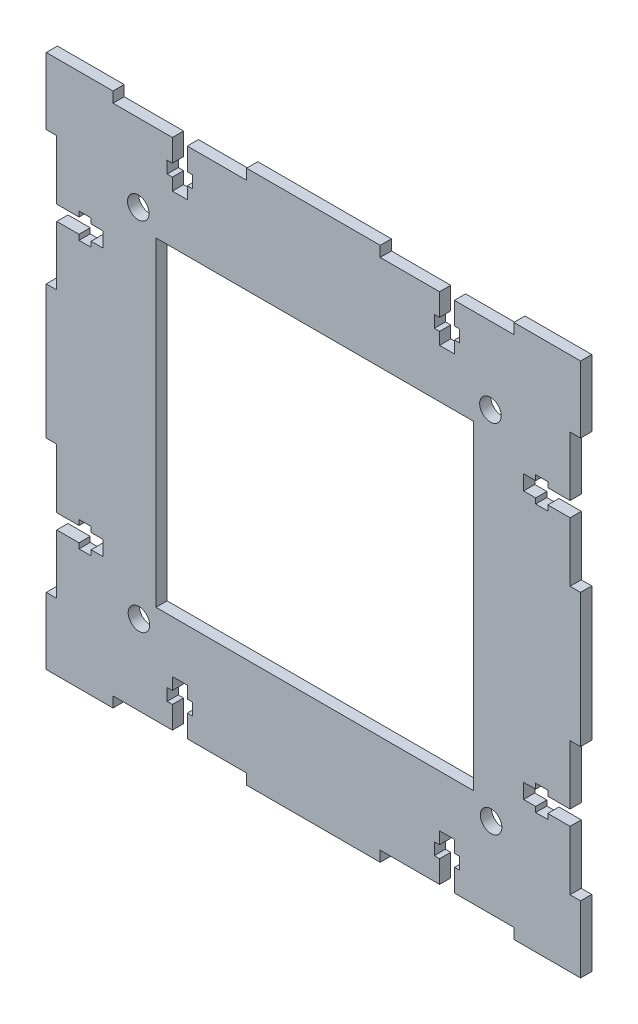
SolidWorks part; units mm, degrees
ref_plane "Front Plane" through (0, 0, 0) normal (0, 0, 1) x (1, 0, 0)
ref_plane "Top Plane" through (0, 0, 0) normal (0, 1, 0) x (1, 0, 0)
ref_plane "Right Plane" through (0, 0, 0) normal (1, 0, 0) x (0, 0, -1)
sketch "Sketch1" plane through (0, 0, 0) normal (0, 0, 1) x (1, 0, 0)
  line L5 (31.0877, 278.8269) -> (31.0877, 188.1807)
  line L12 (31.0877, 188.1807) -> (121.0608, 188.1807)
  line L13 (121.0608, 278.8269) -> (121.0608, 188.1807)
  line L14 (31.0877, 278.8269) -> (121.0608, 278.8269)
  line L312 (0, 308.795) -> (0, 289.8679)
  line L313 (0, 289.8679) -> (2.9806, 289.8679)
  line L314 (2.9806, 289.8679) -> (2.9806, 273.0521)
  line L315 (2.9806, 273.0521) -> (9.2897, 273.0521)
  line L316 (9.2897, 273.0521) -> (9.2897, 274.5424)
  line L317 (9.2897, 274.5424) -> (12.7174, 274.5424)
  line L318 (12.7174, 274.5424) -> (12.7174, 273.0521)
  line L319 (12.7174, 273.0521) -> (16.1452, 273.0521)
  line L320 (16.1452, 273.0521) -> (16.1452, 268.8295)
  line L321 (16.1452, 268.8295) -> (12.7174, 268.8295)
  line L322 (12.7174, 268.8295) -> (12.7174, 267.3392)
  line L323 (12.7174, 267.3392) -> (9.2897, 267.3392)
  line L324 (9.2897, 267.3392) -> (9.2897, 268.8295)
  line L325 (9.2897, 268.8295) -> (2.9806, 268.8295)
  line L326 (2.9806, 268.8295) -> (2.9806, 252.0137)
  line L327 (2.9806, 252.0137) -> (0, 252.0137)
  line L328 (0, 252.0137) -> (0, 214.1595)
  line L329 (0, 214.1595) -> (2.9806, 214.1595)
  line L330 (2.9806, 214.1595) -> (2.9806, 197.3437)
  line L331 (2.9806, 197.3437) -> (9.2897, 197.3437)
  line L332 (9.2897, 197.3437) -> (9.2897, 198.834)
  line L333 (9.2897, 198.834) -> (12.7174, 198.834)
  line L334 (12.7174, 198.834) -> (12.7174, 197.3437)
  line L335 (12.7174, 197.3437) -> (16.1452, 197.3437)
  line L336 (16.1452, 197.3437) -> (16.1452, 193.1211)
  line L337 (16.1452, 193.1211) -> (12.7174, 193.1211)
  line L338 (12.7174, 193.1211) -> (12.7174, 191.6307)
  line L339 (12.7174, 191.6307) -> (9.2897, 191.6307)
  line L340 (9.2897, 191.6307) -> (9.2897, 193.1211)
  line L341 (9.2897, 193.1211) -> (2.9806, 193.1211)
  line L342 (2.9806, 193.1211) -> (2.9806, 176.3053)
  line L343 (2.9806, 176.3053) -> (0, 176.3053)
  line L344 (0, 176.3053) -> (0, 157.3781)
  line L345 (0, 157.3781) -> (18.9271, 157.3781)
  line L346 (18.9271, 157.3781) -> (18.9271, 160.3588)
  line L347 (18.9271, 160.3588) -> (35.7429, 160.3588)
  line L348 (35.7429, 160.3588) -> (35.7429, 166.6678)
  line L349 (35.7429, 166.6678) -> (34.2526, 166.6678)
  line L350 (34.2526, 166.6678) -> (34.2526, 170.0956)
  line L351 (34.2526, 170.0956) -> (35.7429, 170.0956)
  line L352 (35.7429, 170.0956) -> (35.7429, 173.5233)
  line L353 (35.7429, 173.5233) -> (39.9655, 173.5233)
  line L354 (39.9655, 173.5233) -> (39.9655, 170.0956)
  line L355 (39.9655, 170.0956) -> (41.4558, 170.0956)
  line L356 (41.4558, 170.0956) -> (41.4558, 166.6678)
  line L357 (41.4558, 166.6678) -> (39.9655, 166.6678)
  line L358 (39.9655, 166.6678) -> (39.9655, 160.3588)
  line L359 (39.9655, 160.3588) -> (56.7813, 160.3588)
  line L360 (56.7813, 160.3588) -> (56.7813, 157.3781)
  line L361 (56.7813, 157.3781) -> (94.6355, 157.3781)
  line L362 (94.6355, 157.3781) -> (94.6355, 160.3588)
  line L363 (94.6355, 160.3588) -> (111.4513, 160.3588)
  line L364 (111.4513, 160.3588) -> (111.4513, 166.6678)
  line L365 (111.4513, 166.6678) -> (109.961, 166.6678)
  line L366 (109.961, 166.6678) -> (109.961, 170.0956)
  line L367 (109.961, 170.0956) -> (111.4513, 170.0956)
  line L368 (111.4513, 170.0956) -> (111.4513, 173.5233)
  line L369 (111.4513, 173.5233) -> (115.6739, 173.5233)
  line L370 (115.6739, 173.5233) -> (115.6739, 170.0956)
  line L371 (115.6739, 170.0956) -> (117.1643, 170.0956)
  line L372 (117.1643, 170.0956) -> (117.1643, 166.6678)
  line L373 (117.1643, 166.6678) -> (115.6739, 166.6678)
  line L374 (115.6739, 166.6678) -> (115.6739, 160.3588)
  line L375 (115.6739, 160.3588) -> (132.4897, 160.3588)
  line L376 (132.4897, 160.3588) -> (132.4897, 157.3781)
  line L377 (132.4897, 157.3781) -> (151.4169, 157.3781)
  line L378 (151.4169, 157.3781) -> (151.4169, 176.3053)
  line L379 (151.4169, 176.3053) -> (148.4362, 176.3053)
  line L380 (148.4362, 176.3053) -> (148.4362, 193.1211)
  line L381 (148.4362, 193.1211) -> (142.1272, 193.1211)
  line L382 (142.1272, 193.1211) -> (142.1272, 191.6307)
  line L383 (142.1272, 191.6307) -> (138.6994, 191.6307)
  line L384 (138.6994, 191.6307) -> (138.6994, 193.1211)
  line L385 (138.6994, 193.1211) -> (135.2717, 193.1211)
  line L386 (135.2717, 193.1211) -> (135.2717, 197.3437)
  line L387 (135.2717, 197.3437) -> (138.6994, 197.3437)
  line L388 (138.6994, 197.3437) -> (138.6994, 198.834)
  line L389 (138.6994, 198.834) -> (142.1272, 198.834)
  line L390 (142.1272, 198.834) -> (142.1272, 197.3437)
  line L391 (142.1272, 197.3437) -> (148.4362, 197.3437)
  line L392 (148.4362, 197.3437) -> (148.4362, 214.1595)
  line L393 (148.4362, 214.1595) -> (151.4169, 214.1595)
  line L394 (151.4169, 214.1595) -> (151.4169, 252.0137)
  line L395 (151.4169, 252.0137) -> (148.4362, 252.0137)
  line L396 (148.4362, 252.0137) -> (148.4362, 268.8295)
  line L397 (148.4362, 268.8295) -> (142.1272, 268.8295)
  line L398 (142.1272, 268.8295) -> (142.1272, 267.3392)
  line L399 (142.1272, 267.3392) -> (138.6994, 267.3392)
  line L400 (138.6994, 267.3392) -> (138.6994, 268.8295)
  line L401 (138.6994, 268.8295) -> (135.2717, 268.8295)
  line L402 (135.2717, 268.8295) -> (135.2717, 273.0521)
  line L403 (135.2717, 273.0521) -> (138.6994, 273.0521)
  line L404 (138.6994, 273.0521) -> (138.6994, 274.5424)
  line L405 (138.6994, 274.5424) -> (142.1272, 274.5424)
  line L406 (142.1272, 274.5424) -> (142.1272, 273.0521)
  line L407 (142.1272, 273.0521) -> (148.4362, 273.0521)
  line L408 (148.4362, 273.0521) -> (148.4362, 289.8679)
  line L409 (148.4362, 289.8679) -> (151.4169, 289.8679)
  line L410 (151.4169, 289.8679) -> (151.4169, 308.795)
  line L411 (151.4169, 308.795) -> (132.4897, 308.795)
  line L412 (132.4897, 308.795) -> (132.4897, 305.8144)
  line L413 (132.4897, 305.8144) -> (115.6739, 305.8144)
  line L414 (115.6739, 305.8144) -> (115.6739, 299.5053)
  line L415 (115.6739, 299.5053) -> (117.1643, 299.5053)
  line L416 (117.1643, 299.5053) -> (117.1643, 296.0776)
  line L417 (117.1643, 296.0776) -> (115.6739, 296.0776)
  line L418 (115.6739, 296.0776) -> (115.6739, 292.6498)
  line L419 (115.6739, 292.6498) -> (111.4513, 292.6498)
  line L420 (111.4513, 292.6498) -> (111.4513, 296.0776)
  line L421 (111.4513, 296.0776) -> (109.961, 296.0776)
  line L422 (109.961, 296.0776) -> (109.961, 299.5053)
  line L423 (109.961, 299.5053) -> (111.4513, 299.5053)
  line L424 (111.4513, 299.5053) -> (111.4513, 305.8144)
  line L425 (111.4513, 305.8144) -> (94.6355, 305.8144)
  line L426 (94.6355, 305.8144) -> (94.6355, 308.795)
  line L427 (94.6355, 308.795) -> (56.7813, 308.795)
  line L428 (56.7813, 308.795) -> (56.7813, 305.8144)
  line L429 (56.7813, 305.8144) -> (39.9655, 305.8144)
  line L430 (39.9655, 305.8144) -> (39.9655, 299.5053)
  line L431 (39.9655, 299.5053) -> (41.4558, 299.5053)
  line L432 (41.4558, 299.5053) -> (41.4558, 296.0776)
  line L433 (41.4558, 296.0776) -> (39.9655, 296.0776)
  line L434 (39.9655, 296.0776) -> (39.9655, 292.6498)
  line L435 (39.9655, 292.6498) -> (35.7429, 292.6498)
  line L436 (35.7429, 292.6498) -> (35.7429, 296.0776)
  line L437 (35.7429, 296.0776) -> (34.2526, 296.0776)
  line L438 (34.2526, 296.0776) -> (34.2526, 299.5053)
  line L439 (34.2526, 299.5053) -> (35.7429, 299.5053)
  line L440 (35.7429, 299.5053) -> (35.7429, 305.8144)
  line L441 (35.7429, 305.8144) -> (18.9271, 305.8144)
  line L442 (18.9271, 305.8144) -> (18.9271, 308.795)
  line L443 (18.9271, 308.795) -> (0, 308.795)
  line L624 (75.7084, 308.795) -> (75.7084, 157.3781) construction
  line L625 (0, 233.0866) -> (151.4169, 233.0866) construction
  circle A12 centre (26.0877, 283.8269) radius 3.05
  circle A13 centre (125.8732, 284.0707) radius 3.05
  circle A14 centre (126.0608, 183.1807) radius 3.05
  circle A15 centre (26.2754, 182.9332) radius 3.05
  point P648 (75.7084, 233.0866)
extrude "Boss-Extrude1" add sketch "Sketch1" along normal blind 3.175
